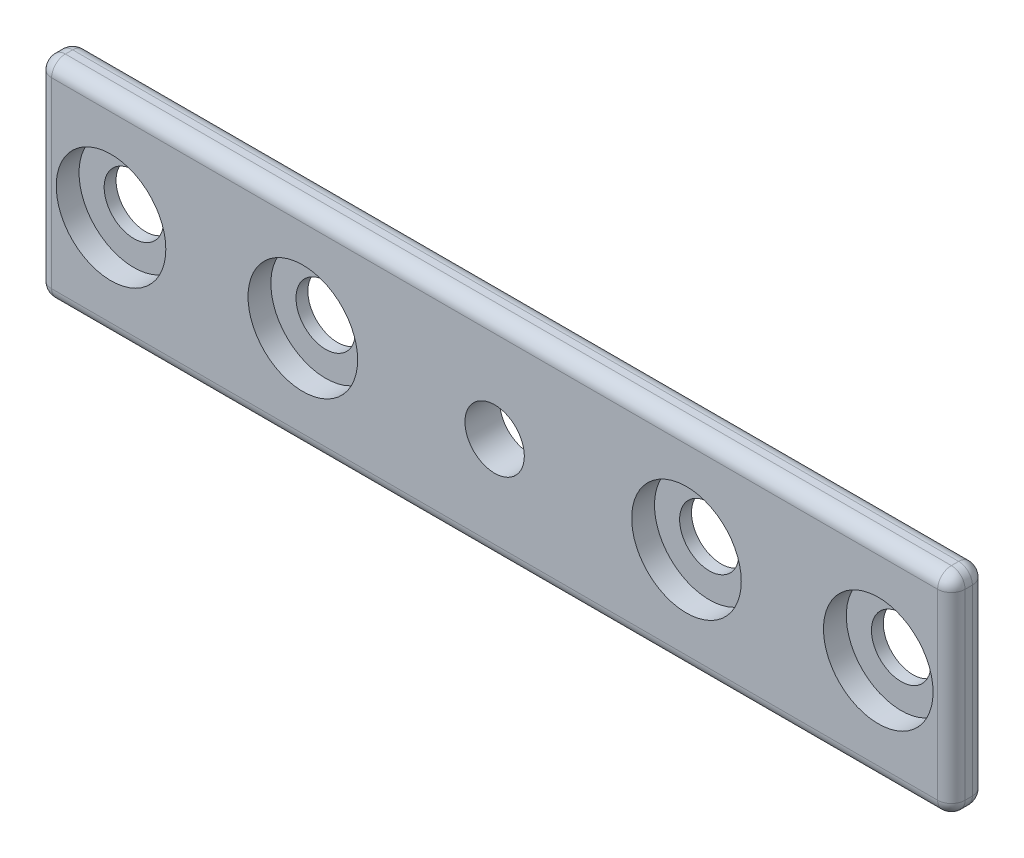
SolidWorks part; units mm, degrees
ref_plane "Front Plane" through (0, 0, 0) normal (0, 0, 1) x (1, 0, 0)
ref_plane "Top Plane" through (0, 0, 0) normal (0, 1, 0) x (1, 0, 0)
ref_plane "Right Plane" through (0, 0, 0) normal (1, 0, 0) x (0, 0, -1)
sketch "Sketch1" plane through (0, 0, 0) normal (0, 0, 1) x (1, 0, 0)
  line L1 (0, 0) -> (100, 0)
  line L2 (0, 0) -> (0, 23)
  line L3 (0, 23) -> (100, 23)
  line L4 (100, 0) -> (100, 23)
  line L5 (0, 0) -> (100, 23) construction
  line L6 (0, 23) -> (100, 0) construction
  point P4 (50, 11.5)
  dimension "D1" = 100
  dimension "D2" = 23
extrude "Boss-Extrude1" add sketch "Sketch1" along normal blind 3.8
sketch "Sketch2" plane through (0, 0, 3.8) normal (0, 0, 1) x (1, 0, 0)
  line L0 (100, 11.5) -> (-4.7879, 11.5) construction
  line L1 (100, 0) -> (100, 23) construction
  line L2 (0, 23) -> (0, 0) construction
  circle A0 centre (8, 11.5) radius 3.25
  circle A1 centre (29, 11.5) radius 3.25
  circle A2 centre (50, 11.5) radius 3.25
  circle A3 centre (71, 11.5) radius 3.25
  circle A4 centre (92, 11.5) radius 3.25
  dimension "D1" = 6.5
  dimension "D2" = 8
  dimension "D3" = 5
extrude "Cut-Extrude1" cut sketch "Sketch2" against normal through all
sketch "Sketch3" plane through (0, 0, 3.8) normal (0, 0, 1) x (1, 0, 0)
  circle A0 centre (8, 11.5) radius 6
  circle A1 centre (29, 11.5) radius 6
  circle A2 centre (71, 11.5) radius 6
  circle A3 centre (92, 11.5) radius 6
  dimension "D1" = 12
  dimension "D2" = 12
  dimension "D3" = 12
  dimension "D4" = 12
extrude "Cut-Extrude5" cut sketch "Sketch3" against normal blind 2.5
fillet "Fillet1" radius 1.5 12 edges at (100, 11.5, 3.8) (100, 11.5, 0) (0, 11.5, 3.8) (0, 11.5, 0) (100, 23, 1.9) (50, 23, 3.8) (0, 23, 1.9) (50, 23, 0) (0, 0, 1.9) (50, 0, 3.8) (100, 0, 1.9) (50, 0, 0)
